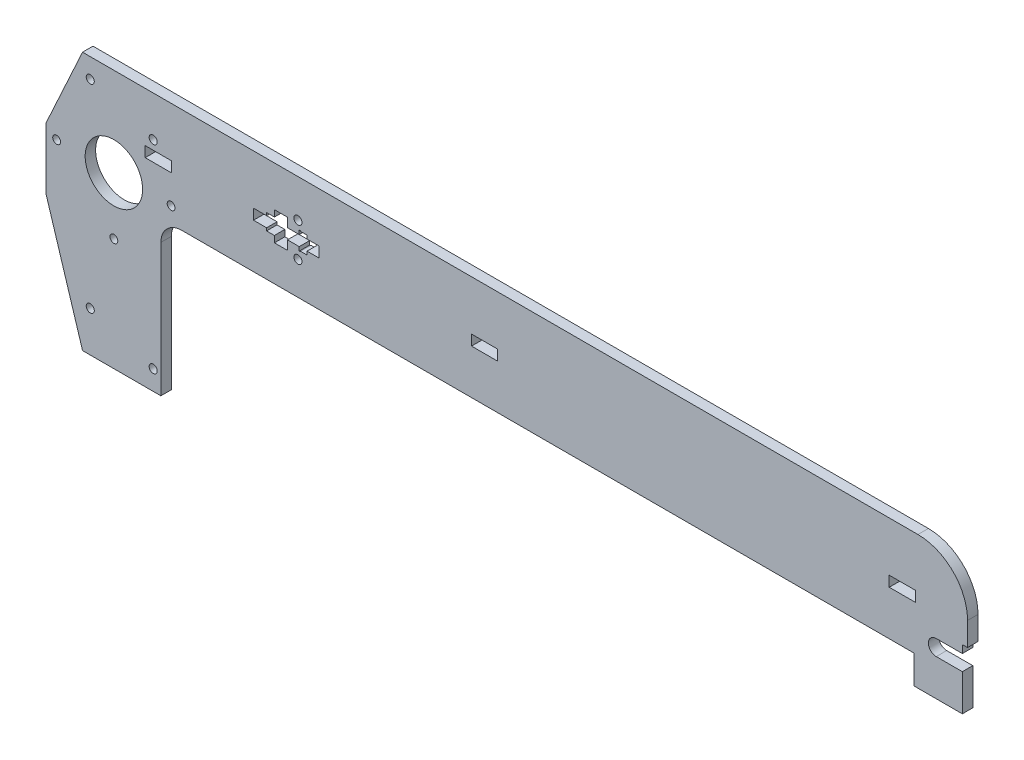
SolidWorks part; units mm, degrees
material "Mahogany"
ref_plane "Front Plane" through (0, 0, 0) normal (0, 0, 1) x (1, 0, 0)
ref_plane "Top Plane" through (0, 0, 0) normal (0, 1, 0) x (1, 0, 0)
ref_plane "Right Plane" through (0, 0, 0) normal (1, 0, 0) x (0, 0, -1)
sketch "Sketch1" plane through (0, 0, 0) normal (0, 0, 1) x (1, 0, 0)
  line L0 (-26, 0) -> (29.6968, 0) construction
  line L1 (-7.5, 22.5) -> (13.5, 22.5) construction
  line L2 (-12, 34) -> (-26, 3.5)
  line L3 (-26, -20) -> (-12, -65)
  line L4 (-7.5, 34) -> (13.5, 34) construction
  line L5 (308, 34) -> (-12, 34)
  line L6 (21.9203, 0) -> (0, 21.9203) construction
  line L7 (0, 21.9203) -> (-21.9203, 0) construction
  line L8 (-21.9203, 0) -> (0, -21.9203) construction
  line L9 (0, -21.9203) -> (21.9203, 0) construction
  line L10 (306.5, -6.1) -> (306.5, -17)
  line L11 (18, -45) -> (18, -65)
  line L12 (-26, 3.5) -> (-26, -20)
  line L13 (315, 3) -> (325, 3)
  line L14 (306.5, -17) -> (325, -17)
  line L15 (18, -6.1) -> (306.5, -6.1)
  line L16 (28, -12.1) -> (52.932, -12.1) construction
  line L17 (325, 6) -> (325, 3)
  line L18 (3, 33.9068) -> (3, -43) construction
  line L19 (-7.5, 33.9068) -> (13.5, 33.9068) construction
  line L20 (-7.5, 34) -> (-7.5, 11) construction
  line L21 (-12, -65) -> (18, -65)
  line L22 (-7.5, 11) -> (13.5, 11) construction
  line L23 (315, -3) -> (325, -3)
  line L24 (325, -3) -> (325, -17)
  line L25 (325, 6) -> (327, 6)
  line L26 (327, 6) -> (327, 15)
  line L27 (18, -45) -> (18, -6.1)
  line L28 (13.5, 34) -> (13.5, 11) construction
  line L29 (12, 15) -> (12, 11)
  line L30 (12, 15) -> (22, 15)
  line L31 (27, 72.5933) -> (67, 72.5933) construction
  line L32 (137, 11) -> (147, 11)
  line L33 (137, 11) -> (137, 15)
  line L34 (12, 11) -> (22, 11)
  line L35 (22, 15) -> (22, 11)
  line L36 (137, 15) -> (147, 15)
  line L37 (147, 11) -> (147, 15)
  line L38 (297, 11) -> (307, 11)
  line L39 (297, 11) -> (297, 15)
  line L40 (297, 15) -> (307, 15)
  line L41 (307, 11) -> (307, 15)
  line L42 (27, 72.5933) -> (27, -36.7256) construction
  line L43 (27, -36.7256) -> (67, -36.7256) construction
  line L44 (67, 72.5933) -> (67, -36.7256) construction
  line L45 (-7.5, -53.5) -> (13.5, -53.5) construction
  line L46 (-7.5, -65) -> (13.5, -65) construction
  line L47 (-7.5, -65) -> (-7.5, -42) construction
  line L48 (-7.5, -42) -> (13.5, -42) construction
  line L49 (13.5, -65) -> (13.5, -42) construction
  line L50 (78.5, 13) -> (53.5, 13) construction
  line L51 (53.5, 11) -> (58.5, 11)
  line L52 (53.5, 11) -> (53.5, 15)
  line L53 (53.5, 15) -> (58.5, 15)
  line L54 (78.5, 11) -> (78.5, 15)
  line L55 (70.5, 19.5) -> (70.5, 6.5) construction
  line L56 (66.5, 7.5) -> (61.5, 7.5)
  line L57 (66.5, 7.5) -> (66.5, 11)
  line L58 (61.5, 7.5) -> (61.5, 9.95)
  line L59 (66.5, 18.5) -> (61.5, 18.5)
  line L60 (66.5, 7.5) -> (61.5, 18.5) construction
  line L61 (61.5, 7.5) -> (66.5, 18.5) construction
  line L62 (66.5, 11) -> (71, 11)
  line L63 (66.5, 15) -> (66.5, 18.5)
  line L64 (66.5, 15) -> (71, 15)
  line L65 (61.5, 16.05) -> (61.5, 18.5)
  line L66 (71.5, 16.3) -> (74, 16.3)
  line L67 (71.5, 16.5) -> (71.5, 16.3)
  line L68 (74, 16.3) -> (74, 15)
  line L69 (71.5, 9.7) -> (74, 9.7)
  line L70 (71.5, 16.3) -> (74, 9.7) construction
  line L71 (74, 16.3) -> (71.5, 9.7) construction
  line L72 (71.5, 9.7) -> (71.5, 9.5)
  line L73 (74, 11) -> (78.5, 11)
  line L74 (74, 11) -> (74, 9.7)
  line L75 (74, 15) -> (78.5, 15)
  line L76 (71.5, 16.5) -> (71, 16.5)
  line L77 (71, 16.5) -> (71, 15)
  line L78 (61.5, 16.05) -> (58.5, 16.05)
  line L79 (71, 11) -> (71, 9.5)
  line L80 (71, 9.5) -> (71.5, 9.5)
  line L81 (58.5, 16.05) -> (58.5, 15)
  line L82 (58.5, 11) -> (58.5, 9.95)
  line L83 (58.5, 9.95) -> (61.5, 9.95)
  circle A0 centre (3, 25) radius 1.55 construction
  circle A1 centre (0, 0) radius 15.5 construction
  circle A2 centre (0, 21.9203) radius 1.5 construction
  circle A3 centre (21.9203, 0) radius 1.5
  circle A4 centre (0, -21.9203) radius 1.5
  circle A5 centre (-21.9203, 0) radius 1.5
  circle A6 centre (0, 0) radius 5.5 construction
  arc A7 (327, 15) -> (308, 34) centre (308, 15) ccw
  circle A8 centre (0, 0) radius 11
  circle A9 centre (-9.05, 26.5) radius 1.55
  circle A10 centre (3, -57) radius 1.55 construction
  arc A11 (315, 3) -> (315, -3) centre (315, 0) ccw
  circle A12 centre (72, -1.1) radius 5 construction
  circle A13 centre (22, 29) radius 5 construction
  circle A14 centre (22, 29) radius 1.5 construction
  circle A15 centre (72, -1.1) radius 1.5 construction
  circle A16 centre (15.05, 18.5) radius 1.55
  circle A17 centre (-9.05, -49.5) radius 1.55
  circle A18 centre (15.05, -57.5) radius 1.55
  circle A19 centre (70.5, 6.5) radius 1.55
  circle A20 centre (70.5, 19.5) radius 1.55
  point P18 (26.8692, -2.8293)
  point P19 (26.8692, 2.8293)
  point P100 (64, 13)
  point P108 (70.5, 13)
  point P109 (72.75, 13)
  dimension "D2" = 31
  dimension "D3" = 3
  dimension "D4" = 11
  dimension "D12" = 22
  dimension "D20" = 3.1
  dimension "D22" = 8
  dimension "D25" = 3
  dimension "D28" = 6
  dimension "D32" = 10
  dimension "D38" = 3
  dimension "D14" = 20
  dimension "D41" = 3.1
  dimension "D44" = 56.5
  dimension "D45" = 3.1
  dimension "D53" = 7
  dimension "D7" = 15
  dimension "D11" = 18.5
  dimension "D17" = 30
  dimension "D8" = 65
  dimension "D9" = 34
  dimension "D5" = 3
  dimension "D6" = 6.1
  dimension "D10" = 6
  dimension "D13" = 327
  dimension "D15" = 23
  dimension "D16" = 20
  dimension "D18" = 23.5
  dimension "D19" = 26
  dimension "D21" = 9
  dimension "D23" = 21.1
  dimension "D24" = 10.9
  dimension "D26" = 10
  dimension "D27" = 2
  dimension "D29" = 67
  dimension "D30" = 12
  dimension "D31" = 40
  dimension "D33" = 4
  dimension "D34" = 10
  dimension "D35" = 20
  dimension "D36" = 180
  dimension "D37" = 21
  dimension "D39" = 4
  dimension "D40" = 4
  dimension "D42" = 4
  dimension "D43" = 4
  dimension "D46" = 13
  dimension "D47" = 8
  dimension "D48" = 11
  dimension "D49" = 4
  dimension "D50" = 5
  dimension "D51" = 11
  dimension "D52" = 25
  dimension "D54" = 2.5
  dimension "D55" = 6.6
  dimension "D56" = 0.5
  dimension "D57" = 4.5
  dimension "D58" = 6.1
  dimension "D59" = 3
extrude "Boss-Extrude1" add sketch "Sketch1" along normal blind 4
fillet "Fillet1" radius 8 1 edges at (18, -6.1, 2)
